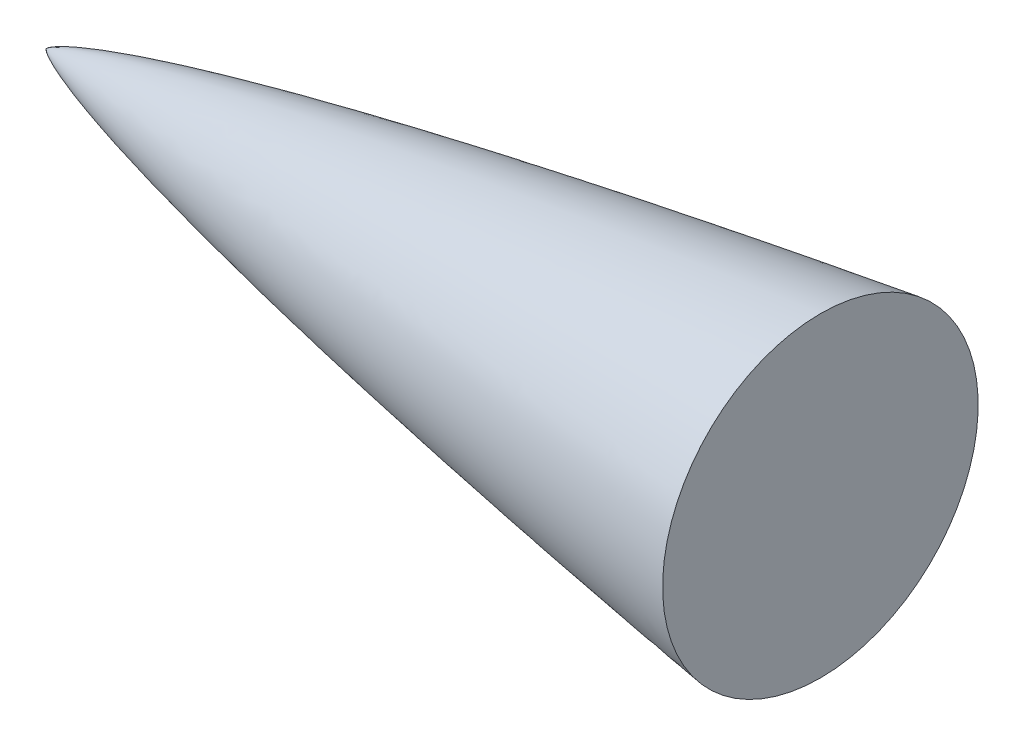
SolidWorks part; units mm, degrees
material "6061-T6 (SS)"
ref_plane "Front" through (0, 0, 0) normal (0, 0, 1) x (1, 0, 0)
ref_plane "Top" through (0, 0, 0) normal (0, 1, 0) x (1, 0, 0)
ref_plane "Right" through (0, 0, 0) normal (1, 0, 0) x (0, 0, -1)
sketch "Sketch7" plane through (0, 0, 0) normal (0, 0, 1) x (1, 0, 0)
  line L0 (0, 0) -> (1126.623, 0) construction
  line L1 (762, 83.8413) -> (762, 0)
  line L2 (0, 0) -> (762, 0)
  spline S0 degree 4 poles (0, 0) (0.0025, 0.0077) (0.0085, 0.0225) (0.0254, 0.0499) (0.0657, 0.1001) (0.1275, 0.1632) (0.2121, 0.2373) (0.3323, 0.3316) (0.4768, 0.4341) (0.6465, 0.5448) (0.8414, 0.663) (1.1269, 0.8263) (1.5727, 1.0629) (2.3354, 1.4323) (3.7109, 2.0298) (6.1546, 2.9698) (10.668, 4.4903) (18.9995, 6.9173) (33.3858, 10.5209) (58.2147, 15.8817) (92.5014, 22.2364) (134.3472, 29.0669) (181.2323, 35.9138) (228.1994, 42.1676) (275.2294, 47.9287) (322.3096, 53.2619) (369.4323, 58.2049) (416.5919, 62.7813) (463.7847, 67.0021) (511.0079, 70.8684) (558.2595, 74.3704) (605.5383, 77.4858) (646.9303, 79.8373) (682.4256, 81.5392) (710.8634, 82.6554) (729.8529, 83.259) (745.3094, 83.6328) (754.8465, 83.7859) (759.6154, 83.8349) (762, 83.8413) knots 0 0 0 0 0 0.000042 0.000084 0.000167 0.000334 0.000501 0.000668 0.000962 0.001257 0.001556 0.001855 0.002675 0.003884 0.005967 0.009662 0.016304 0.028676 0.05114 0.086868 0.148544 0.21022 0.271896 0.333573 0.395249 0.456925 0.518602 0.580278 0.641954 0.70363 0.765307 0.826983 0.888659 0.919497 0.950336 0.975168 0.987584 1 1 1 1 1 construction
  spline S1 degree 4 poles (0, 0) (0.0025, 0.0077) (0.0085, 0.0225) (0.0254, 0.0499) (0.0657, 0.1001) (0.1275, 0.1632) (0.2121, 0.2373) (0.3323, 0.3316) (0.4768, 0.4341) (0.6465, 0.5448) (0.8414, 0.663) (1.1269, 0.8263) (1.5727, 1.0629) (2.3354, 1.4323) (3.7109, 2.0298) (6.1546, 2.9698) (10.668, 4.4903) (18.9995, 6.9173) (33.3858, 10.5209) (58.2147, 15.8817) (92.5014, 22.2364) (134.3472, 29.0669) (181.2323, 35.9138) (228.1994, 42.1676) (275.2294, 47.9287) (322.3096, 53.2619) (369.4323, 58.2049) (416.5919, 62.7813) (463.7847, 67.0021) (511.0079, 70.8684) (558.2595, 74.3704) (605.5383, 77.4858) (646.9303, 79.8373) (682.4256, 81.5392) (710.8634, 82.6554) (729.8529, 83.259) (745.3094, 83.6328) (754.8465, 83.7859) (759.6154, 83.8349) (762, 83.8413) knots 0 0 0 0 0 0.000042 0.000084 0.000167 0.000334 0.000501 0.000668 0.000962 0.001257 0.001556 0.001855 0.002675 0.003884 0.005967 0.009662 0.016304 0.028676 0.05114 0.086868 0.148544 0.21022 0.271896 0.333573 0.395249 0.456925 0.518602 0.580278 0.641954 0.70363 0.765307 0.826983 0.888659 0.919497 0.950336 0.975168 0.987584 1 1 1 1 1
revolve "Revolve3" add sketch "Sketch7" angle 360 about L0
sketch "Sketch8" plane through (762, 0, 0) normal (1, 0, 0) x (0, 0, -1)
  circle A0 centre (0, 0) radius 83.8413 construction
  circle A1 centre (0, 0) radius 83.8413
extrude "Boss-Extrude1" add sketch "Sketch8" along normal blind 10.16
ref_plane "Plane1" through (162.56, 0, 0) normal (1, 0, 0) x (0, 0, -1)
sketch "Sketch9" plane through (162.56, 0, 0) normal (1, 0, 0) x (0, 0, -1)
  circle A0 centre (0, 0) radius 117.4613
extrude "Cut-Extrude1" cut sketch "Sketch9" along normal blind 681.99
